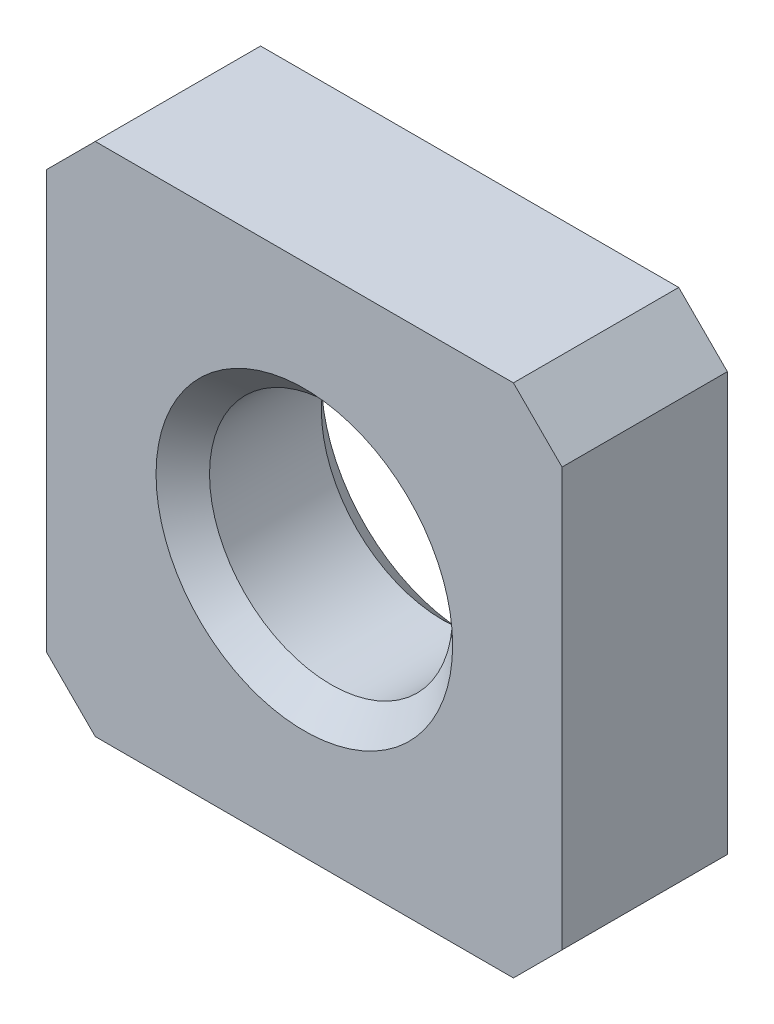
SolidWorks part; units mm, degrees
ref_plane "Front" through (0, 0, 0) normal (0, 0, 1) x (1, 0, 0)
ref_plane "Top" through (0, 0, 0) normal (0, 1, 0) x (1, 0, 0)
ref_plane "Right" through (0, 0, 0) normal (1, 0, 0) x (0, 0, -1)
sketch "草图1" plane through (0, 0, 0) normal (0, 0, 1) x (1, 0, 0)
  line L1 (-2.65, -2.65) -> (2.65, -2.65)
  line L2 (-2.65, -2.65) -> (-2.65, 2.65)
  line L3 (-2.65, 2.65) -> (2.65, 2.65)
  line L4 (2.65, -2.65) -> (2.65, 2.65)
  line L5 (-2.65, -2.65) -> (2.65, 2.65) construction
  line L6 (-2.65, 2.65) -> (2.65, -2.65) construction
  point P0 (0, 0)
  dimension "D1" = 5.3
  dimension "D2" = 45
extrude "凸台-拉伸1" add sketch "草图1" along normal blind 1.7
hole_wizard "M3 螺纹孔1" positions "草图2" profile "草图3" tap size "M3" standard "GB" end condition through all
sketch "草图2" plane through (0, 0, 1.7) normal (0, 0, 1) x (1, 0, 0)
  point P0 (0, 0)
sketch "草图3" plane through (0, 0, 1.7) normal (1, 0, 0) x (0, -1, 0)
  line L0 (0, 0) -> (0, 1.7)
  line L1 (0, 1.7) -> (1.525, 1.7)
  line L2 (1.25, 1.425) -> (1.25, 0.275)
  line L3 (1.25, 0.275) -> (1.525, 0)
  line L5 (1.525, 0) -> (0, 0)
  line L6 (-1.25, 0.275) -> (-1.525, 0) construction
  line L7 (1.525, 1.7) -> (1.25, 1.425)
  line L8 (-1.525, 1.7) -> (-1.25, 1.425) construction
  line L11 (0, -6.35) -> (0, 107.95) construction
  dimension "通孔螺纹孔钻头直径" = 2.5
  dimension "通孔螺纹孔钻头深度" = 1.7
  dimension "近端锥形沉头孔直径" = 3.05
  dimension "近端锥形沉头孔角度" = 90
  dimension "远端锥形沉头孔直径" = 3.05
  dimension "远端锥形沉头孔角度" = 90
cosmetic thread "孔螺蚊线1" parameters "D2"=3
chamfer "倒角1" distance 0.5 angle 45 4 edges at (-2.65, -2.65, 0.85) (-2.65, 2.65, 0.85) (2.65, -2.65, 0.85) (2.65, 2.65, 0.85)
